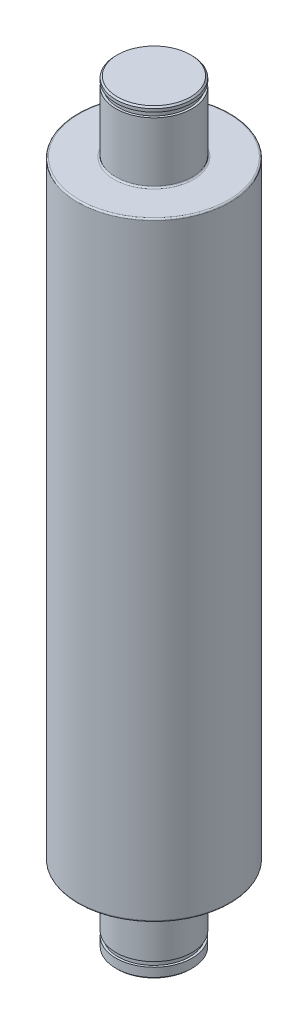
SolidWorks part; units mm, degrees
ref_plane "Plan de face" through (0, 0, 0) normal (0, 0, 1) x (1, 0, 0)
ref_plane "Plan de dessus" through (0, 0, 0) normal (0, 1, 0) x (1, 0, 0)
ref_plane "Plan de droite" through (0, 0, 0) normal (1, 0, 0) x (0, 0, -1)
sketch "Esquisse1" plane through (0, 0, 0) normal (0, 1, 0) x (1, 0, 0)
  circle A0 centre (0, 0) radius 50
  dimension "D1" = 100
extrude "Boss.-Extru.1" add sketch "Esquisse1" along normal blind 400
sketch "Esquisse2" plane through (0, 400, 0) normal (0, 1, 0) x (1, 0, 0)
  circle A0 centre (0, 0) radius 25
  dimension "D1" = 50
extrude "Boss.-Extru.2" add sketch "Esquisse2" along normal blind 46
sketch "Esquisse3" plane through (0, 0, 0) normal (0, -1, 0) x (1, 0, 0)
  circle A0 centre (0, 0) radius 25
  dimension "D1" = 50
extrude "Boss.-Extru.3" add sketch "Esquisse3" along normal blind 50
fillet "Congé1" radius 1 4 edges at (0, 0, 25) (0, 0, 50) (0, 400, 50) (0, 400, 25)
sketch "Esquisse4" plane through (0, 446, 0) normal (0, 1, 0) x (1, 0, 0)
  circle A0 centre (0, 0) radius 25
  circle A1 centre (0, 0) radius 23.5
  dimension "D1" = 50
  dimension "D2" = 47
extrude "Enlèv. mat.-Extru.1" cut sketch "Esquisse4" against normal blind 3.2 from offset 3 offset against normal yes
ref_axis "Axe1" through (0, -50, 0) along (0, 1, 0)
sketch "Esquisse6" plane through (0, 0, 0) normal (0, 0, 1) x (1, 0, 0)
  line L0 (-25, -50) -> (25, -50) construction
  line L1 (28.7495, -40) -> (23.5, -40)
  line L2 (28.7495, -40) -> (28.7495, -43.2)
  line L3 (28.7495, -43.2) -> (23.5, -43.2)
  line L4 (23.5, -40) -> (23.5, -43.2)
  line L5 (25, -50) -> (25, -1) construction
  dimension "D1" = 10
  dimension "D2" = 3.2
  dimension "D3" = 1.5
revolve "Enlèvement de matière-Révolution1" cut sketch "Esquisse6" angle 360 about axis through (0, -50, 0) along (0, 1, 0)
chamfer "Chanfrein1" distance 1 angle 45 2 edges at (0, -50, -25) (0, 446, 25)
sketch "Esquisse7" plane through (0, -50, 0) normal (0, -1, 0) x (1, 0, 0)
  circle A0 centre (0, 0) radius 13
extrude "Enlèv. mat.-Extru.2" cut sketch "Esquisse7" against normal blind 40
sketch "Esquisse8" plane through (0, -50, 0) normal (0, -1, 0) x (1, 0, 0)
  line L1 (-3, 15) -> (3, 15)
  line L2 (-3, 15) -> (-3, 10)
  line L3 (-3, 10) -> (3, 10)
  line L4 (3, 15) -> (3, 10)
  dimension "D1" = 5
  dimension "D2" = 10
  dimension "D3" = 6
  dimension "D4" = 3
extrude "Enlèv. mat.-Extru.3" cut sketch "Esquisse8" against normal blind 38
